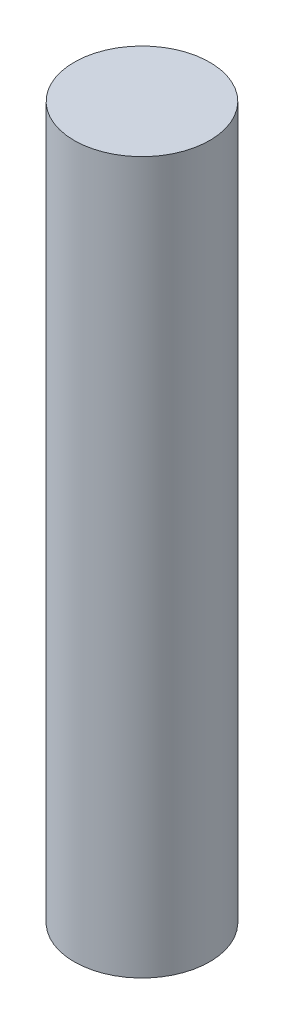
SolidWorks part; units mm, degrees
ref_plane "Front Plane" through (0, 0, 0) normal (0, 0, 1) x (1, 0, 0)
ref_plane "Top Plane" through (0, 0, 0) normal (0, 1, 0) x (1, 0, 0)
ref_plane "Right Plane" through (0, 0, 0) normal (1, 0, 0) x (0, 0, -1)
sketch "Sketch1" plane through (0, 0, 0) normal (0, 1, 0) x (1, 0, 0)
  circle A0 centre (0, 0) radius 0.89
  dimension "D1" = 1.78
extrude "Boss-Extrude1" add sketch "Sketch1" along normal blind 9.34
